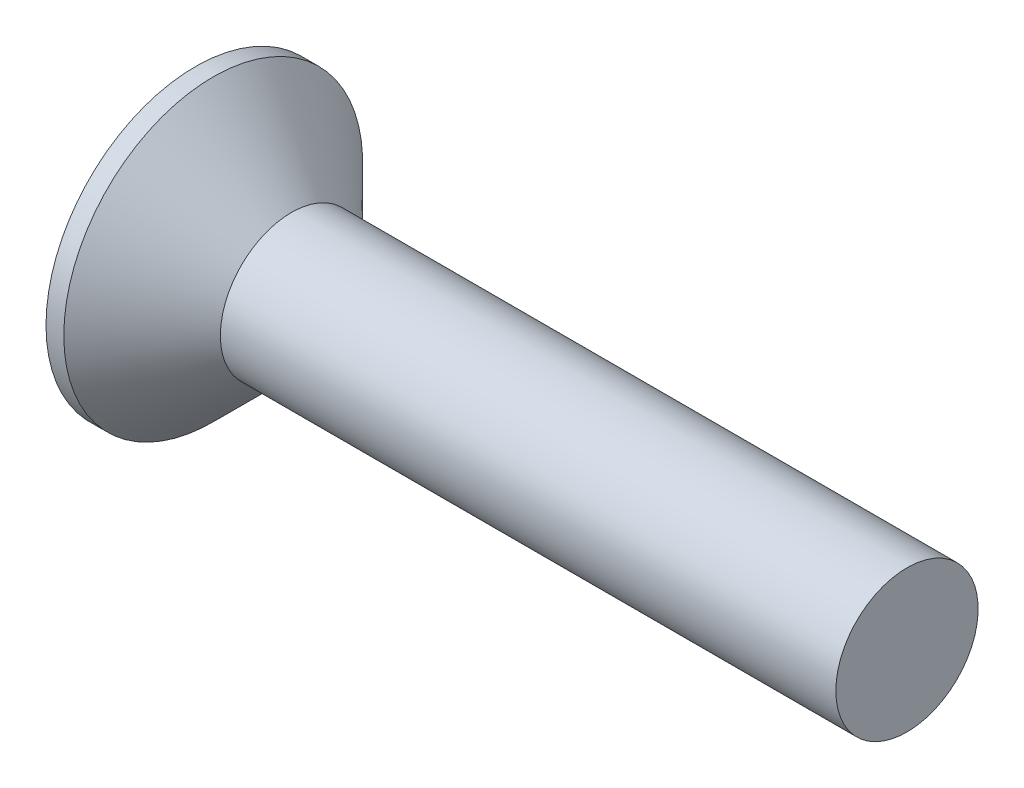
SolidWorks part; units mm, degrees
revolve "Base-Revolve" add sketch "BodySke" angle 360 about L5
sketch "BodySke" plane through (0, 0, 0) normal (0, 0, 1) x (1, 0, 0)
  line L0 (0, 0) -> (0, 4.2)
  line L1 (0, 4.2) -> (0.5, 4.2)
  line L2 (2.7, 2) -> (20, 2)
  line L3 (20, 2) -> (20, 0)
  line L4 (20, 0) -> (0, 0)
  line L5 (-6.35, 0) -> (82.55, 0) construction
  line L6 (2.7, -2) -> (20, -2) construction
  line L7 (0.5, -4.2) -> (2.7, -2) construction
  line L8 (0.5, 4.2) -> (2.7, 2)
  line L9 (0, -4.2) -> (0.5, -4.2) construction
  line L10 (3.4, 3.5875) -> (3.4, -5.9375) construction
  line L11 (0, 6.35) -> (0, -3.175) construction
  dimension "Head_ang" = 90
cosmetic thread "ThreadCosmetic" [suppressed] parameters "Thread_length"=10.8, "Thread_minor"=3.22
extrude "Slot" [suppressed] cut sketch "Sketch2" against normal blind 1.3
sketch "Sketch2" plane through (0, 0, 0) normal (-1, 0, 0) x (0, 0, 1)
  line L0 (-4.2, -0.75) -> (4.2, -0.75)
  line L1 (-4.2, -0.75) -> (-4.2, 0.75)
  line L2 (4.2, 0.75) -> (-4.2, 0.75)
  line L3 (4.2, 0.75) -> (4.2, -0.75)
  dimension "Slot_width" = 1.5
  dimension "D1" = 0.5
  dimension "D2" = 5.5
  dimension "D3" = 2.75
ref_plane "Plane1" through (0, 0, 0) normal (0, 0, 1) x (1, 0, 0)
ref_plane "Plane2" through (0, 0, 0) normal (0, 1, 0) x (1, 0, 0)
ref_plane "Plane3" through (0, 0, 0) normal (1, 0, 0) x (0, 0, -1)
sketch "Sketch3" plane through (0, 0, 0) normal (-1, 0, 0) x (0, 0, 1)
  line L0 (-0.48, 2.23) -> (0.48, 2.23)
  line L1 (0.48, 2.23) -> (0.48, -2.23)
  line L2 (0.48, -2.23) -> (-0.48, -2.23)
  line L3 (-0.48, -2.23) -> (-0.48, 2.23)
  dimension "D1" = 1.55
  dimension "D2" = 0.395
ref_plane "Plane4" through (2.65, 0, 0) normal (-1, 0, 0) x (0, 0, 1)
sketch "Sketch4" plane through (2.65, 0, 0) normal (-1, 0, 0) x (0, 0, 1)
  line L0 (-0.24, 0.24) -> (0.24, 0.24)
  line L3 (0.24, 0.24) -> (0.24, -0.24)
  line L4 (0.24, -0.24) -> (-0.24, -0.24)
  line L5 (-0.24, -0.24) -> (-0.24, 0.24)
  dimension "D2" = 0.395
  dimension "D1" = 0.395
  dimension "D3" = 0.1975
  dimension "D4" = 0.1975
loft "Cross" cut profiles "Sketch3", "Sketch4"
pattern_circular "CirPattern1" count 2 every 90 about axis through (0, 0, 0) along (1, 0, 0) of "Cross"
sketch "ThdSchSke" plane through (0, 0, 0) normal (0, 0, 1) x (1, 0, 0)
  line L0 (3.4, -1.61) -> (3.1269, -2)
  line L1 (3.4, -1.61) -> (3.6731, -2)
  line L2 (3.6731, -2) -> (3.6731, -2.5)
  line L3 (-3.175, 0) -> (5.1513, 0) construction
  line L5 (3.6731, -2.5) -> (3.1269, -2.5)
  line L6 (3.1269, -2.5) -> (3.1269, -2)
  line L7 (0, 4.2) -> (0, -4.2) construction
  dimension "Thread_minor" = 2.439
  dimension "Diameter" = 3
  dimension "Start" = 2.2
revolve "ThreadSchematic" [suppressed] cut sketch "ThdSchSke" angle 360 about L3
pattern_linear "ThdSchPat" [suppressed]
equation "\"D1@Sketch3\" = \"Cross_dia@Sketch3\" / 2"
equation "\"D2@Sketch3\" = \"Cross_width@Sketch3\" / 2"
equation "\"D1@Sketch4\" = \"Cross_width@Sketch3\" *.5"
equation "\"D2@Sketch4\" = \"D1@Sketch4\""
equation "\"D4@Sketch4\" = \"D2@Sketch4\" / 2"
equation "\"D3@Sketch4\" = \"D1@Sketch4\" / 2"
equation "\"D1@Sketch2\" = \"Slot_width@Sketch2\" / 2"
equation "\"D2@Sketch2\" = \"Head_dia@BodySke\""
equation "\"D3@Sketch2\" = \"D2@Sketch2\" / 2"
equation "\"Thread_length@ThreadCosmetic\" = ((sgn( (\"Length@BodySke\" - \"Advance@BodySke\" - \"Head_ht@BodySke\" ) - \"Thread_nom@BodySke\" )-1)*( (\"Length@BodySke\" - \"Advance@BodySke\" - \"Head_ht@BodySke\" ) - \"Thread_nom@BodySke\" ))/-2+ \"Thread_nom@BodySke\""
equation "\"Thread_minor@ThdSchSke\" = \"Thread_minor@ThreadCosmetic\""
equation "\"Diameter@ThdSchSke\" = \"Diameter@BodySke\""
equation "\"Overcut@ThdSchSke\" = \"Diameter@BodySke\" * 1.25"
equation "\"Start@ThdSchSke\" = 0.000001 + \"Length@BodySke\" - \"Thread_length@ThreadCosmetic\"  '---Countersunk---"
equation "\"Num_threads@ThdSchPat\" = int( \"Thread_length@ThreadCosmetic\" / \"Advance@BodySke\" + 0.999 )  + 1"
equation "\"Advance@ThdSchPat\" = \"Thread_length@ThreadCosmetic\" /  (\"Num_threads@ThdSchPat\" - 1) 'relax it"
